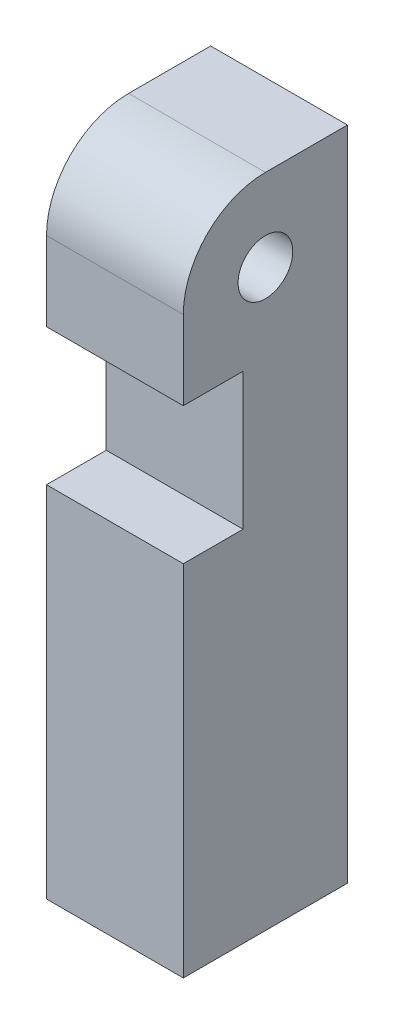
SolidWorks part; units mm, degrees
ref_plane "Front Plane" through (0, 0, 0) normal (0, 0, 1) x (1, 0, 0)
ref_plane "Top Plane" through (0, 0, 0) normal (0, 1, 0) x (1, 0, 0)
ref_plane "Right Plane" through (0, 0, 0) normal (1, 0, 0) x (0, 0, -1)
sketch "Elevator Paddle" plane through (0, 0, 0) normal (1, 0, 0) x (0, 0, -1)
  line L0 (3.81, 3.81) -> (3.81, -26.67)
  line L1 (3.81, -26.67) -> (-3.81, -26.67)
  line L2 (-3.81, -26.67) -> (-3.81, -10.016)
  line L3 (-6.4983, 38.1) -> (3.6147, 38.1)
  line L4 (3.81, 3.81) -> (0, 3.81)
  line L5 (-3.81, -3.666) -> (-1.0375, -3.666)
  line L6 (-1.0375, -3.666) -> (-1.0375, -10.016)
  line L7 (-1.0375, -10.016) -> (-3.81, -10.016)
  line L8 (-3.81, -3.666) -> (-3.81, 0)
  line L9 (1.735, 3.81) -> (1.735, -26.67) construction
  line L10 (-3.81, -12.8389) -> (1.735, -12.8389) construction
  line L11 (-1.0375, -10.016) -> (-1.0375, -12.8389) construction
  circle A0 centre (0, 0) radius 1.27
  arc A1 (0, 3.81) -> (-3.81, 0) centre (0, 0) ccw
  point P17 (-1.0375, -12.8389)
  dimension "D3" = 2.54
  dimension "D1" = 2.54
  dimension "D2" = 2.54
  dimension "D4" = 25.4
  dimension "D6" = 2.7725
  dimension "D7" = 2.54
  dimension "D5" = 6.35
  dimension "D8" = 2.075
extrude "Boss-Extrude1" add sketch "Elevator Paddle" along normal blind 6.35
equation "\"Ball Diameter\"= 1.75in"
equation "\"Sheet Thickness\"= 0.25in"
equation "\"Screw Diameter\"= .17in"
equation "\"Robot Diameter\"= 14in"
equation "\"Castor Screw Diameter\"= 0.22in"
equation "\"Wheel Diameter\" = 4in"
equation "\"Nut Diameter\" = 8.4mm"
equation "\"Nut Height\" = 2.9mm"
equation "\"Screw Height\" = 0.55in"
equation "\"D1@Boss-Extrude1\"=\"Sheet Thickness\""
equation "\"Pulley Diameter\" = 1in"
equation "\"Reactor Height\" = 14in"
equation "\"Elevator Height\" = 11.5in"
equation "\"Elevator Width\" = \"Ball Diameter\" + 0.25in"
equation "\"Elevator Bearing Diameter\" = sqr(2*(\"Sheet Thickness\"^2)) + 0.2in"
equation "\"Elevator Axle Endcap Diameter\" = \"Pulley Diameter\" + 0.25in"
equation "\"Elevator Axle Length\" = \"Elevator Width\" + 8*\"Sheet Thickness\""
equation "\"Elevator Clearance from Axis\" = (\"Pulley Diameter\"/2) + \"Ball Diameter\" + 0.5in"
equation "\"D5@Elevator Paddle\"=\"Sheet Thickness\""
equation "\"D6@Elevator Paddle\"=\"Sheet Thickness\"/2"
equation "\"D8@Elevator Paddle\"=(\"Elevator Axle Endcap Diameter\"-\"Pulley Diameter\")/2 - 1.1mm"
